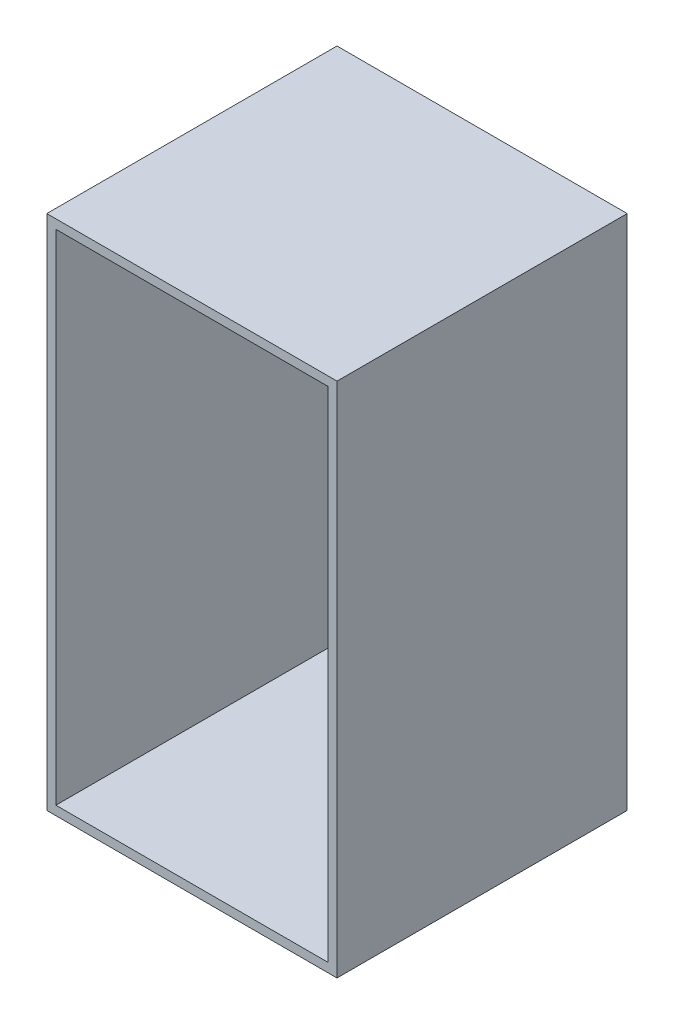
SolidWorks part; units mm, degrees
material "99.5% Aluminum Oxide"
ref_plane "Front Plane" through (0, 0, 0) normal (0, 0, 1) x (1, 0, 0)
ref_plane "Top Plane" through (0, 0, 0) normal (0, 1, 0) x (1, 0, 0)
ref_plane "Right Plane" through (0, 0, 0) normal (1, 0, 0) x (0, 0, -1)
sketch "Sketch1" plane through (0, 0, 0) normal (0, 0, 1) x (1, 0, 0)
  line L0 (260, 510) -> (320, 570) construction
  line L1 (-260, -510) -> (260, -510) construction
  line L2 (-260, -510) -> (-260, 510) construction
  line L3 (-260, 510) -> (260, 510) construction
  line L4 (260, -510) -> (260, 510) construction
  line L5 (-260, -510) -> (260, 510) construction
  line L6 (-260, 510) -> (260, -510) construction
  line L7 (-320, -570) -> (320, -570)
  line L8 (-320, -570) -> (-320, 570)
  line L9 (-320, 570) -> (320, 570)
  line L10 (320, -570) -> (320, 570)
  line L11 (-320, -570) -> (320, 570) construction
  line L12 (-320, 570) -> (320, -570) construction
  point P0 (0, 0)
  point P6 (0, 0)
  dimension "D1" = 520
  dimension "D2" = 1020
  dimension "D3" = 45
  dimension "D4" = 60
  dimension "D5" = 640
extrude "Boss-Extrude1" add sketch "Sketch1" along normal blind 640
shell "Shell1" thickness 20
